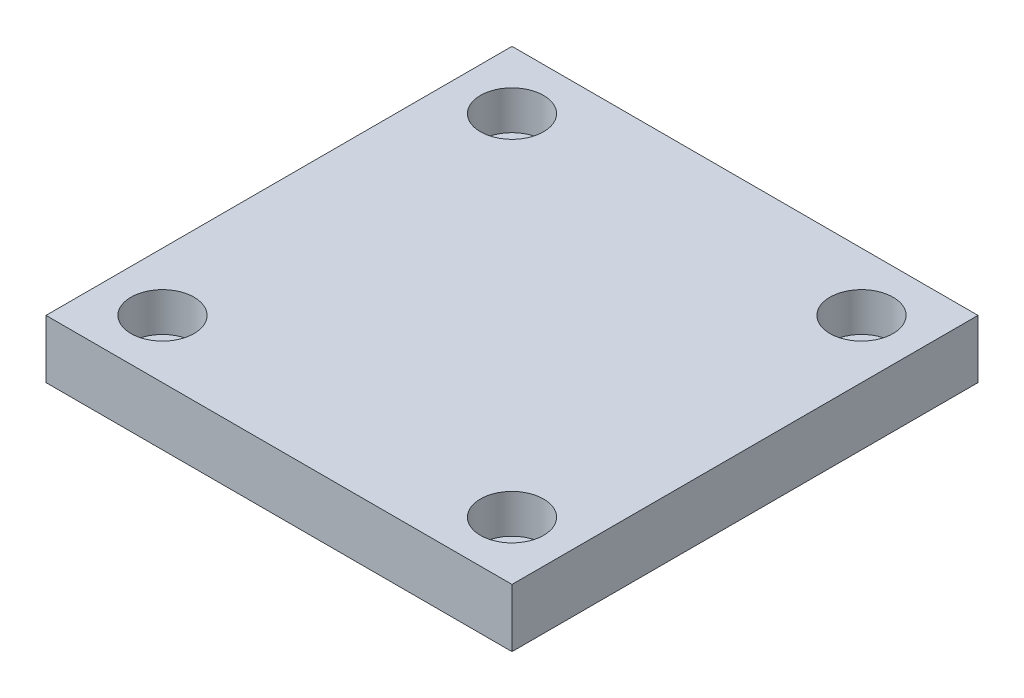
SolidWorks part; units mm, degrees
ref_plane "Front Plane" through (0, 0, 0) normal (0, 0, 1) x (1, 0, 0)
ref_plane "Top Plane" through (0, 0, 0) normal (0, 1, 0) x (1, 0, 0)
ref_plane "Right Plane" through (0, 0, 0) normal (1, 0, 0) x (0, 0, -1)
sketch "Sketch1" plane through (0, 0, 0) normal (0, 1, 0) x (1, 0, 0)
  line L0 (57.15, 57.15) -> (76.2, 57.15) construction
  line L1 (0, 0) -> (76.2, 0)
  line L2 (0, 0) -> (0, 76.2)
  line L3 (0, 76.2) -> (76.2, 76.2)
  line L4 (76.2, 0) -> (76.2, 76.2)
  line L5 (57.15, 57.15) -> (57.15, 76.2) construction
  dimension "D1" = 19.05
  dimension "D3" = 76.2
extrude "Boss-Extrude1" add sketch "Sketch1" along normal blind 19.05
hole_wizard "CBORE for 1/2 Socket Head Cap Screw1" positions "Sketch3" profile "Sketch2" counterbore size "1/2" standard "ANSI Inch" end condition through all
sketch "Sketch3" plane through (0, 19.05, 0) normal (0, 1, 0) x (1, 0, 0)
  point P0 (57.15, 57.15)
sketch "Sketch2" plane through (57.15, 19.05, -57.15) normal (1, 0, 0) x (0, 0, 1)
  line L0 (0, 0) -> (0, 19.05)
  line L1 (0, 19.05) -> (6.7462, 19.05)
  line L3 (6.7462, 19.05) -> (6.7462, 12.7)
  line L4 (6.7462, 12.7) -> (10.3187, 12.7)
  line L5 (10.3187, 12.7) -> (10.3187, 0)
  line L7 (10.3187, 0) -> (0, 0)
  line L11 (0, -6.35) -> (0, 107.95) construction
  dimension "Thru Hole Dia." = 13.4925
  dimension "Thru Hole Depth" = 19.05
  dimension "C'Bore Dia." = 20.6375
  dimension "C'Bore Depth" = 12.7
mirror "Mirror1" about plane through (0, 19.05, 0) normal (0, 0, -1) of bodies 104 101
mirror "Mirror2" about plane through (0, 19.05, 0) normal (1, 0, 0) of bodies 102
